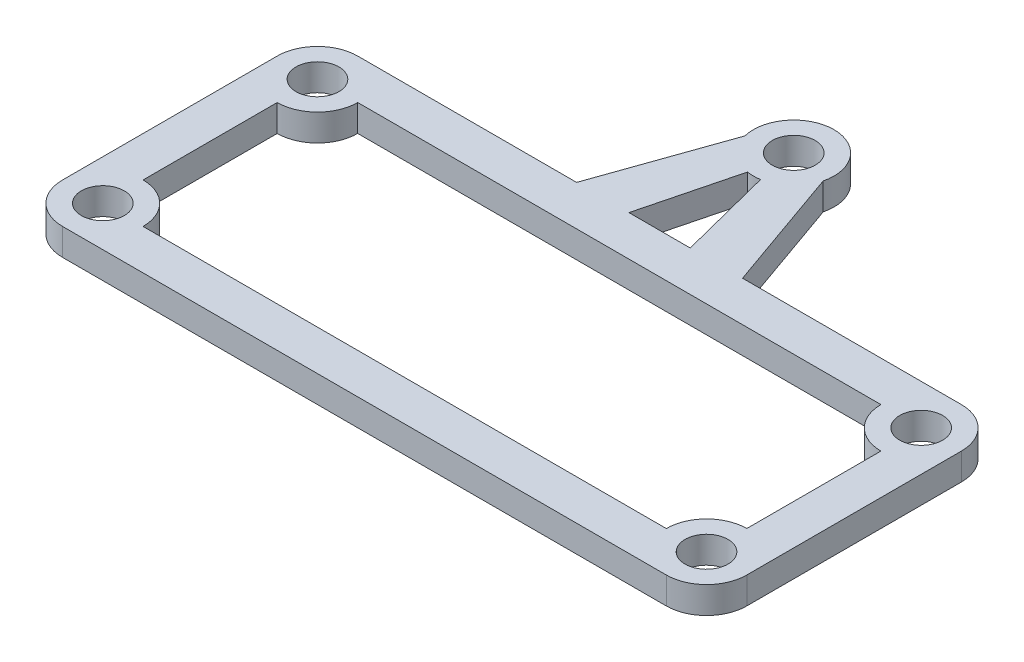
SolidWorks part; units mm, degrees
ref_plane "Front" through (0, 0, 0) normal (0, 0, 1) x (1, 0, 0)
ref_plane "Top" through (0, 0, 0) normal (0, 1, 0) x (1, 0, 0)
ref_plane "Right" through (0, 0, 0) normal (1, 0, 0) x (0, 0, -1)
sketch "Sketch1" plane through (0, 0, 0) normal (0, 1, 0) x (1, 0, 0)
  line L0 (-0.4874, 18.0399) -> (-2.2854, 11)
  line L1 (-19.5, -8) -> (19.5, -8)
  line L2 (-22.5, -5) -> (-22.5, 5)
  line L5 (-19.6734, -6.995) -> (19.6734, 6.995) construction
  line L6 (6.185, 11) -> (22.5, 11)
  line L7 (-2.9122, 20.2795) -> (-6.185, 11)
  line L8 (2.9122, 20.2795) -> (6.185, 11)
  line L9 (-22.5, 11) -> (-6.185, 11)
  line L10 (-25.5, 8) -> (-25.5, -8)
  line L11 (-22.5, -11) -> (22.5, -11)
  line L12 (25.5, -8) -> (25.5, 8)
  line L13 (-2.2854, 11) -> (2.2854, 11)
  line L14 (-19.6734, 6.995) -> (19.6734, -6.995) construction
  line L15 (-19.5, 8) -> (19.5, 8)
  line L16 (22.5, -5) -> (22.5, 5)
  line L17 (2.2854, 11) -> (0.4874, 18.0399)
  circle A0 centre (-22.5, 8) radius 1.6
  circle A1 centre (-22.5, -8) radius 1.6
  circle A2 centre (22.5, -8) radius 1.6
  circle A3 centre (22.5, 8) radius 1.6
  circle A4 centre (0, 21) radius 1.6
  arc A5 (2.9122, 20.2795) -> (-2.9122, 20.2795) centre (0, 21) ccw
  arc A6 (-22.5, 5) -> (-19.5, 8) centre (-22.5, 8) ccw
  arc A7 (-19.5, -8) -> (-22.5, -5) centre (-22.5, -8) ccw
  arc A8 (19.5, 8) -> (22.5, 5) centre (22.5, 8) ccw
  arc A9 (22.5, -5) -> (19.5, -8) centre (22.5, -8) ccw
  arc A10 (-22.5, 11) -> (-25.5, 8) centre (-22.5, 8) ccw
  arc A11 (25.5, 8) -> (22.5, 11) centre (22.5, 8) ccw
  arc A12 (22.5, -11) -> (25.5, -8) centre (22.5, -8) ccw
  arc A13 (-25.5, -8) -> (-22.5, -11) centre (-22.5, -8) ccw
  arc A14 (-0.4874, 18.0399) -> (0.4874, 18.0399) centre (0, 21) ccw
  point P0 (0, 0)
extrude "Boss-Extrude1" add sketch "Sketch1" along normal blind 2
